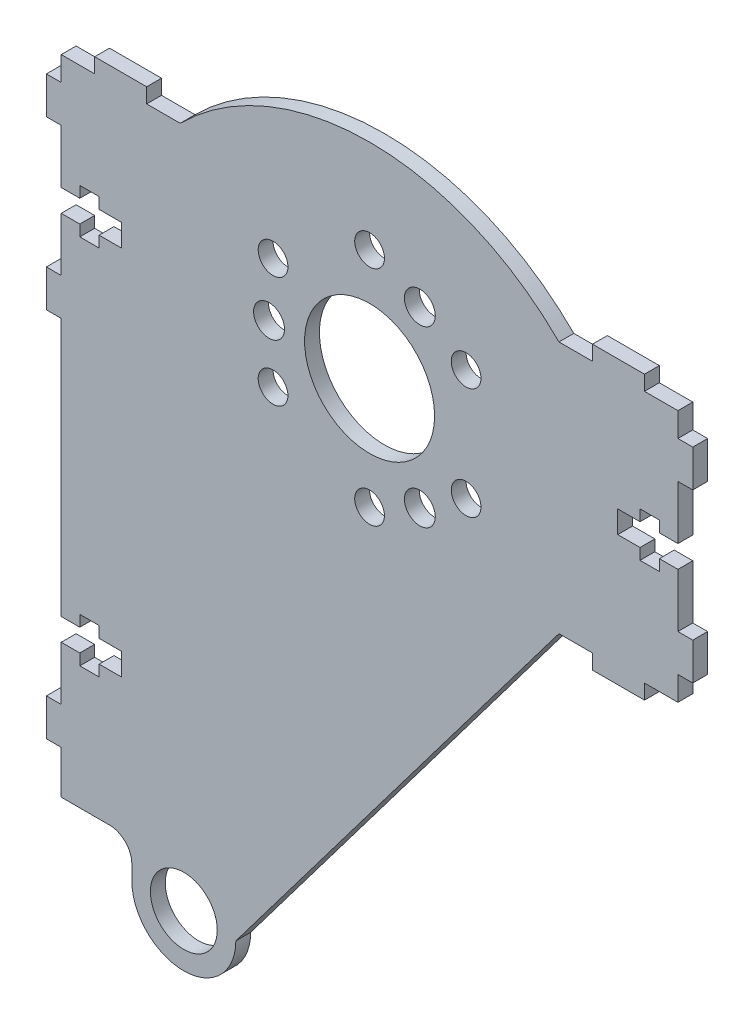
SolidWorks part; units mm, degrees
ref_plane "前视基准面" through (0, 0, 0) normal (0, 0, 1) x (1, 0, 0)
ref_plane "上视基准面" through (0, 0, 0) normal (0, 1, 0) x (1, 0, 0)
ref_plane "右视基准面" through (0, 0, 0) normal (1, 0, 0) x (0, 0, -1)
sketch "草图1" plane through (0, 0, 0) normal (0, 0, 1) x (1, 0, 0)
  line L0 (41.5, 13.75) -> (41.5, 17)
  line L205 (-30, 17) -> (-25.489, 17)
  line L310 (-37, 19) -> (-30, 19)
  line L325 (-30, 17) -> (-30, 19)
  line L326 (-37, 19) -> (-37, 17)
  line L337 (-41.5, 1.5) -> (-41.5, 8.75)
  line L338 (-41.5, 8.75) -> (-43.5, 8.75)
  line L340 (-43.5, 13.75) -> (-41.5, 13.75)
  line L341 (-41.5, 13.75) -> (-41.5, 17)
  line L346 (-41.5, -1.5) -> (-41.5, -8.75)
  line L372 (43.5, -8.75) -> (43.5, -13.75)
  line L373 (43.5, 13.75) -> (43.5, 8.75)
  line L380 (41.5, -1.5) -> (41.5, -8.75)
  line L381 (41.5, -8.75) -> (43.5, -8.75)
  line L384 (-43.5, 13.75) -> (-43.5, 8.75)
  line L386 (41.5, 17) -> (37, 17)
  line L388 (43.5, 13.75) -> (41.5, 13.75)
  line L389 (41.5, 8.75) -> (43.5, 8.75)
  line L390 (41.5, 1.5) -> (41.5, 8.75)
  line L391 (37, 19) -> (37, 17)
  line L392 (30, 17) -> (30, 19)
  line L393 (37, 19) -> (30, 19)
  line L394 (30, 17) -> (25.489, 17)
  line L396 (43.5, -13.75) -> (41.5, -13.75)
  line L397 (41.5, -13.75) -> (41.5, -17)
  line L398 (-39, -1.5) -> (-39, -3)
  line L399 (-33.4, 1.5) -> (-33.4, -1.5)
  line L400 (-39, 1.5) -> (-39, 3)
  line L401 (-41.5, 1.5) -> (-39, 1.5)
  line L402 (-39, -3) -> (-36.4, -3)
  line L403 (-36.4, -3) -> (-36.4, -1.5)
  line L404 (-36.4, -1.5) -> (-33.4, -1.5)
  line L405 (-36.4, 1.5) -> (-33.4, 1.5)
  line L406 (-36.4, 3) -> (-36.4, 1.5)
  line L407 (-39, 3) -> (-36.4, 3)
  line L408 (-39, -1.5) -> (-41.5, -1.5)
  line L409 (39, -1.5) -> (41.5, -1.5)
  line L410 (39, 3) -> (36.4, 3)
  line L411 (36.4, 3) -> (36.4, 1.5)
  line L412 (36.4, 1.5) -> (33.4, 1.5)
  line L413 (36.4, -1.5) -> (33.4, -1.5)
  line L414 (36.4, -3) -> (36.4, -1.5)
  line L415 (39, -3) -> (36.4, -3)
  line L416 (41.5, 1.5) -> (39, 1.5)
  line L417 (39, 1.5) -> (39, 3)
  line L418 (33.4, 1.5) -> (33.4, -1.5)
  line L419 (39, -1.5) -> (39, -3)
  line L423 (-41.5, -8.75) -> (-43.5, -8.75)
  line L424 (-43.5, -8.75) -> (-43.5, -13.75)
  line L425 (-43.5, -13.75) -> (-41.5, -13.75)
  line L439 (37, -17) -> (41.5, -17)
  line L440 (-41.5, 17) -> (-37, 17)
  line L441 (-41.5, -13.75) -> (-41.5, -17)
  line L447 (37, -17) -> (37, -19)
  line L448 (37, -19) -> (30, -19)
  line L449 (30, -19) -> (30, -17)
  line L450 (30, -17) -> (25.489, -17)
  line L452 (-41.5, -51.4979) -> (-41.5, -58.7479)
  line L453 (-39, -51.4979) -> (-39, -52.9979)
  line L454 (-33.4, -48.4979) -> (-33.4, -51.4979)
  line L455 (-39, -48.4979) -> (-39, -46.9979)
  line L456 (-41.5, -48.4979) -> (-39, -48.4979)
  line L457 (-39, -52.9979) -> (-36.4, -52.9979)
  line L458 (-36.4, -52.9979) -> (-36.4, -51.4979)
  line L459 (-36.4, -51.4979) -> (-33.4, -51.4979)
  line L460 (-36.4, -48.4979) -> (-33.4, -48.4979)
  line L461 (-36.4, -46.9979) -> (-36.4, -48.4979)
  line L462 (-39, -46.9979) -> (-36.4, -46.9979)
  line L463 (-39, -51.4979) -> (-41.5, -51.4979)
  line L464 (-41.5, -58.7479) -> (-43.5, -58.7479)
  line L465 (-43.5, -58.7479) -> (-43.5, -63.7479)
  line L466 (-43.5, -63.7479) -> (-41.5, -63.7479)
  line L471 (-41.5, -69.5579) -> (-41.5, -63.7479)
  line L472 (-41.5, -17) -> (-41.5, -48.4979)
  line L474 (-41.5, -69.5579) -> (-35, -69.5579)
  line L475 (-32, -72.5579) -> (-32, -74.5579)
  line L476 (-18, -74.5579) -> (25.489, -17)
  circle A15 centre (0, -15) radius 2
  circle A16 centre (-12.9904, -7.5) radius 2
  circle A17 centre (-12.9904, 7.5) radius 2
  circle A18 centre (0, 15) radius 2
  circle A19 centre (12.9904, 7.5) radius 2
  circle A20 centre (12.9904, -7.5) radius 2
  circle A21 centre (-13.53, 0) radius 2.08
  circle A22 centre (6.765, 11.7173) radius 2.08
  circle A23 centre (6.765, -11.7173) radius 2.08
  circle A24 centre (0, 0) radius 8.75
  arc A27 (-25.489, 17) -> (25.489, 17) centre (0, -8.489) cw
  circle A30 centre (-25, -74.5579) radius 4.5
  arc A35 (-32, -74.5579) -> (-18, -74.5579) centre (-25, -74.5579) ccw
  arc A36 (-32, -72.5579) -> (-35, -69.5579) centre (-35, -72.5579) ccw
  dimension "D1" = 3
  dimension "D3" = 3
  dimension "D2" = 6
extrude "凸台-拉伸2" add sketch "草图1" along normal blind 2
sketch "草图2" plane through (41.5, 0, 0) normal (1, 0, 0) x (0, 0, -1)
  line L0 (-1, 1.5) -> (-1, -1.5)
  line L1 (-2, 1.5) -> (0, 1.5) construction
  line L2 (-2, -1.5) -> (0, -1.5) construction
  circle A0 centre (-1, 0) radius 1.5
sketch "草图3" plane through (-41.5, 0, 0) normal (-1, 0, 0) x (0, 0, 1)
  line L0 (1, 1.5) -> (1, -1.5)
  line L1 (2, 1.5) -> (0, 1.5) construction
  line L2 (2, -1.5) -> (0, -1.5) construction
  circle A0 centre (1, 0) radius 1.5
ref_point "点1"
